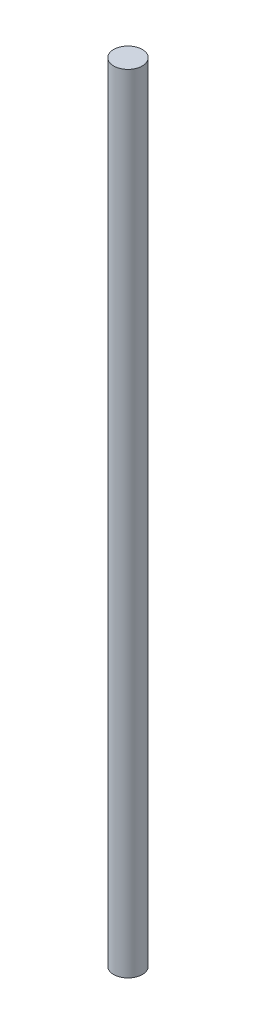
SolidWorks part; units mm, degrees
ref_plane "Front Plane" through (0, 0, 0) normal (0, 0, 1) x (1, 0, 0)
ref_plane "Top Plane" through (0, 0, 0) normal (0, 1, 0) x (1, 0, 0)
ref_plane "Right Plane" through (0, 0, 0) normal (1, 0, 0) x (0, 0, -1)
sketch "Sketch3" plane through (0, 0, 0) normal (0, 1, 0) x (1, 0, 0)
  circle A0 centre (0, 0) radius 5.005
  dimension "D1" = 10.01
extrude "Boss-Extrude1" add sketch "Sketch3" along normal blind 275
